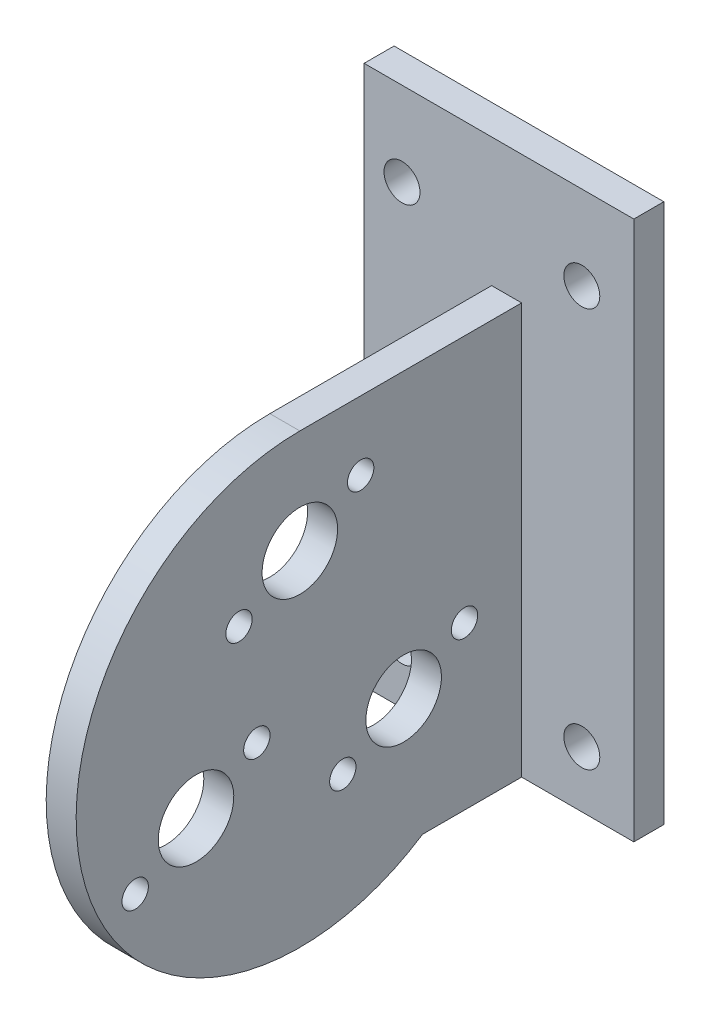
SolidWorks part; units mm, degrees
ref_plane "Front Plane" through (0, 0, 0) normal (0, 0, 1) x (1, 0, 0)
ref_plane "Top Plane" through (0, 0, 0) normal (0, 1, 0) x (1, 0, 0)
ref_plane "Right Plane" through (0, 0, 0) normal (1, 0, 0) x (0, 0, -1)
sketch "Sketch1" plane through (268.4978, 0, 0) normal (-1, 0, 0) x (0, 0, 1)
  circle A0 centre (-4.7857, -8.9806) radius 1.397 construction
  circle A1 centre (-17.676, -1.5384) radius 1.397 construction
  circle A4 centre (-28.6745, 17.5116) radius 1.397 construction
  circle A5 centre (-15.7842, 10.0694) radius 1.397 construction
  circle A6 centre (-4.7857, -8.9806) radius 1.397
  circle A7 centre (-17.676, -1.5384) radius 1.397
  circle A8 centre (-26.7828, -8.9806) radius 1.397
  circle A9 centre (-39.673, -1.5384) radius 1.397
  circle A10 centre (-28.6745, 17.5116) radius 1.397
  circle A11 centre (-15.7842, 10.0694) radius 1.397
  circle A12 centre (-22.2294, 1.0905) radius 23.6982
  arc A13 (-25.9254, -13.4834) -> (-40.5304, -13.4834) centre (-33.2279, -5.2595) ccw construction
  arc A16 (-3.9284, -13.4834) -> (-18.5334, -13.4834) centre (-11.2309, -5.2595) ccw construction
  arc A17 (-29.5319, 22.0145) -> (-14.9269, 22.0145) centre (-22.2294, 13.7905) ccw construction
  circle A18 centre (-11.2309, -5.2595) radius 4.0005
  circle A19 centre (-33.2279, -5.2595) radius 4.0005
  circle A20 centre (-22.2294, 13.7905) radius 4.0005
  dimension "D1" = 8.001
  dimension "D2" = 2.794
  dimension "D3" = 2.794
extrude "Boss-Extrude1" add sketch "Sketch1" along normal blind 3.175
sketch "Sketch2" plane through (0, 0, -48.8994) normal (0, 0, 1) x (1, 0, 0)
  line L1 (280.3878, -18.7215) -> (251.8128, -18.7215)
  line L2 (280.3878, -18.7215) -> (280.3878, 38.4285)
  line L3 (280.3878, 38.4285) -> (251.8128, 38.4285)
  line L4 (251.8128, -18.7215) -> (251.8128, 38.4285)
  line L5 (162.3949, 38.4285) -> (302.6128, 38.4285) construction
  line L6 (302.6128, 38.4285) -> (302.6128, -18.4675) construction
  dimension "D1" = 28.575
  dimension "D2" = 22.225
  dimension "D3" = 57.15
extrude "Boss-Extrude2" add sketch "Sketch2" along normal blind 3.175
sketch "Sketch4" plane through (268.4978, 0, 0) normal (1, 0, 0) x (0, 0, -1)
  line L0 (45.7244, -2.0062) -> (45.7244, -18.7215)
  line L1 (45.7244, -18.7215) -> (35.2328, -18.7215)
  line L2 (45.7244, 4.1873) -> (45.7244, 24.7887)
  line L3 (45.7244, 24.7887) -> (22.2294, 24.7887)
  arc A1 (45.7244, 4.1873) -> (45.7244, -2.0062) centre (22.2294, 1.0905) ccw construction
  circle A2 centre (22.2294, 1.0905) radius 23.6982
  arc M5 (45.7244, 4.1873) -> (45.7244, -2.0062) centre (22.2294, 1.0905) ccw
  dimension "D1" = 0
extrude "Boss-Extrude3" add sketch "Sketch4" against normal blind 3.175 contours L1 L0 M5 | L2 L3 M5
sketch "Sketch5" plane through (0, 0, -48.8994) normal (0, 0, -1) x (-1, 0, 0)
  circle A0 centre (-274.8757, -12.7525) radius 1.905
  circle A1 centre (-274.8757, 29.5385) radius 1.905
  circle A2 centre (-255.8257, 29.5385) radius 1.905
  circle A3 centre (-255.8257, -12.7525) radius 1.905
  dimension "D1" = 3.81
extrude "Cut-Extrude2" cut sketch "Sketch5" against normal blind 6.35
